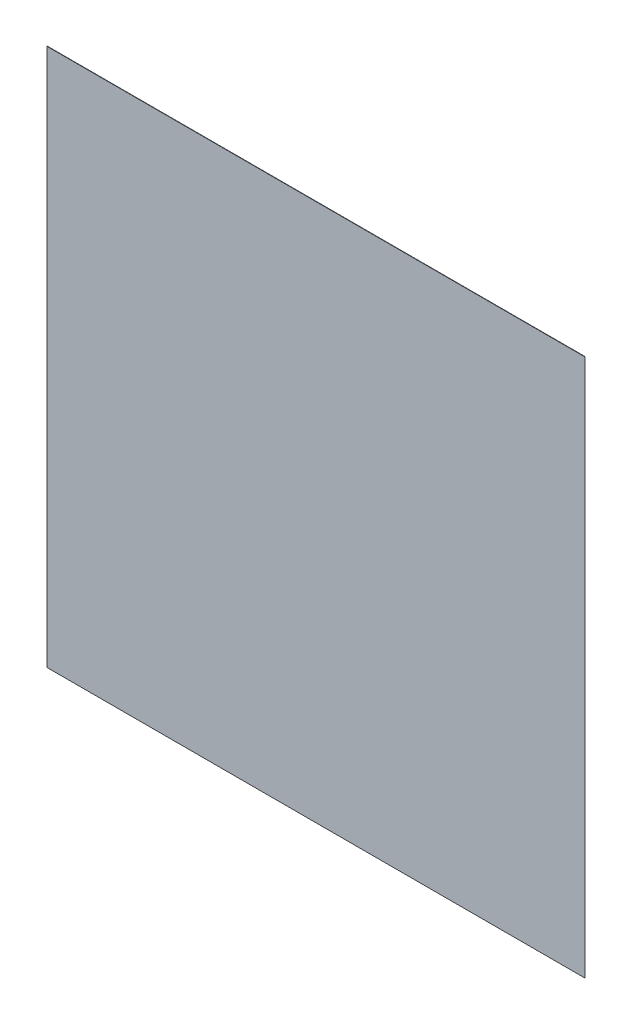
SolidWorks part; units mm, degrees
ref_plane "Front Plane" through (0, 0, 0) normal (0, 0, 1) x (1, 0, 0)
ref_plane "Top Plane" through (0, 0, 0) normal (0, 1, 0) x (1, 0, 0)
ref_plane "Right Plane" through (0, 0, 0) normal (1, 0, 0) x (0, 0, -1)
sketch "Sketch2" plane through (0, 0, 0) normal (0, 0, 1) x (1, 0, 0)
  line L1 (-15, -15) -> (15, -15)
  line L2 (-15, -15) -> (-15, 15)
  line L3 (-15, 15) -> (15, 15)
  line L4 (15, -15) -> (15, 15)
  line L5 (0, 15) -> (0, -15) construction
  line L6 (-15, 0) -> (15, 0) construction
  point P1 (0, 0)
  dimension "D1" = 30
  dimension "D2" = 30
extrude "Boss-Extrude1" add sketch "Sketch2" along normal blind 0.02
